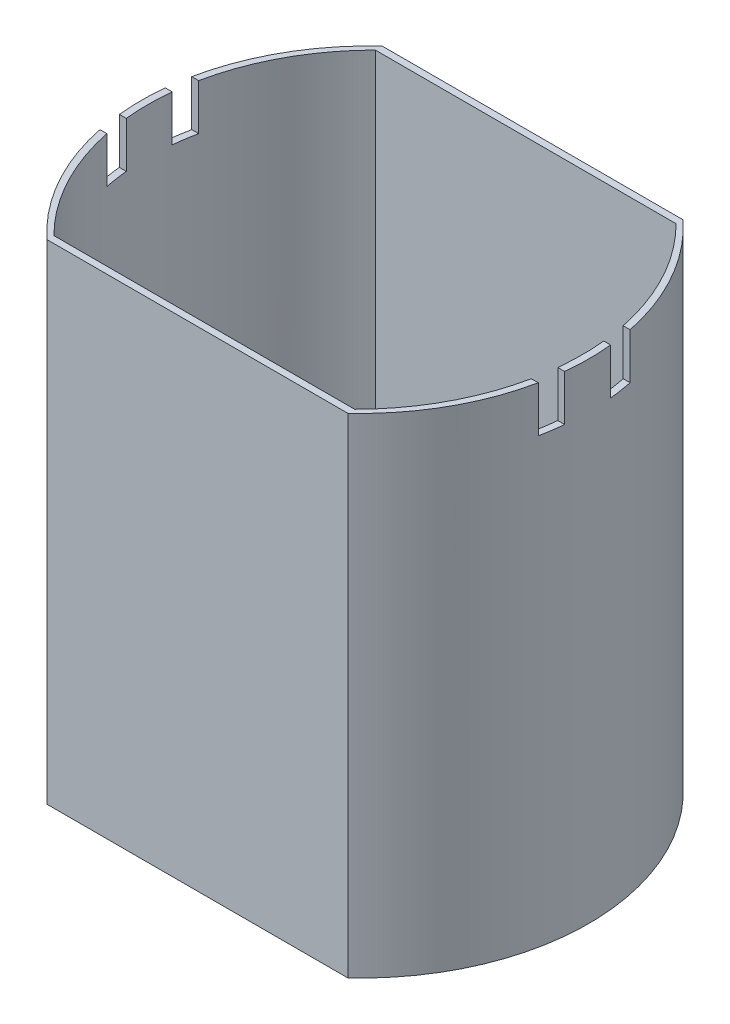
SolidWorks part; units mm, degrees
ref_plane "Front Plane" through (0, 0, 0) normal (0, 0, 1) x (1, 0, 0)
ref_plane "Top Plane" through (0, 0, 0) normal (0, 1, 0) x (1, 0, 0)
ref_plane "Right Plane" through (0, 0, 0) normal (1, 0, 0) x (0, 0, -1)
sketch "Sketch2" plane through (0, 0, 0) normal (0, 1, 0) x (1, 0, 0)
  line L0 (-6.55, 7.3) -> (6.55, 7.3)
  line L1 (-6.55, -7.3) -> (6.55, -7.3)
  line L2 (0, 72.3564) -> (0, -62.3762) construction
  line L3 (-6.55, 7) -> (6.55, 7)
  line L4 (-6.55, -7) -> (6.55, -7)
  line L5 (9.75, 12.0601) -> (9.75, -10.9078) construction
  arc A0 (6.55, 7.3) -> (6.55, -7.3) centre (-0.1766, 0) cw
  arc A1 (6.55, 7) -> (6.55, -7) centre (-0.45, 0) cw
  arc A2 (-6.55, 7) -> (-6.55, -7) centre (0.45, 0) ccw
  arc A3 (-6.55, 7.3) -> (-6.55, -7.3) centre (0.1766, 0) ccw
  point P2 (0, 7.3)
  point P11 (0, -7.3)
  point P13 (0, 7)
  point P19 (0, -7)
  dimension "D1" = 7.3
  dimension "D2" = 7.3
  dimension "D3" = 6.55
  dimension "D4" = 0.3
  dimension "D5" = 0.3
  dimension "D6" = 3.2
extrude "Boss-Extrude1" add sketch "Sketch2" along normal blind 21
sketch "Sketch3" plane through (0, 0, 0) normal (0, 1, 0) x (1, 0, 0)
  line L0 (-6.55, 7.3) -> (6.55, 7.3)
  line L1 (6.55, 7.3) -> (-6.55, 7.3) construction
  line L2 (-6.55, -7.3) -> (6.55, -7.3)
  line L3 (-6.55, -7.3) -> (6.55, -7.3) construction
  line L4 (0, 9.8661) -> (0, -9.5895) construction
  circle A2 centre (0, 0) radius 0.9
  arc A3 (6.55, 7.3) -> (6.55, -7.3) centre (-0.1766, 0) cw
  arc A4 (-6.55, 7.3) -> (-6.55, -7.3) centre (0.1766, 0) ccw
  point P5 (0, 7.3)
  point P17 (0, -7.3)
  dimension "D1" = 1.8
extrude "Boss-Extrude2" add sketch "Sketch3" against normal blind 0.3
sketch "Sketch4" plane through (0, 21, 0) normal (0, 1, 0) x (1, 0, 0)
  line L0 (-7.6312, 1) -> (-14.6311, 1)
  line L1 (-14.6311, 1) -> (-14.6311, -1)
  line L2 (-14.6311, -1) -> (-7.5389, -1)
  line L3 (-7.5389, -1) -> (-7.5389, -2)
  line L4 (-7.5389, -2) -> (-15.3846, -2)
  line L5 (-15.3846, -2) -> (-15.3846, 2)
  line L6 (-15.3846, 2) -> (-7.6312, 2)
  line L7 (-7.6312, 2) -> (-7.6312, 1)
  line L8 (0, 10.6393) -> (0, -10.6397) construction
  line L9 (7.6312, 2) -> (7.6312, 1)
  line L10 (15.3846, 2) -> (7.6312, 2)
  line L11 (15.3846, -2) -> (15.3846, 2)
  line L12 (7.5389, -2) -> (15.3846, -2)
  line L13 (7.5389, -1) -> (7.5389, -2)
  line L14 (14.6311, -1) -> (7.5389, -1)
  line L15 (14.6311, 1) -> (14.6311, -1)
  line L16 (7.6312, 1) -> (14.6311, 1)
  dimension "D1" = 1
  dimension "D2" = 1
  dimension "D3" = 1
extrude "Cut-Extrude1" cut sketch "Sketch4" against normal blind 2
